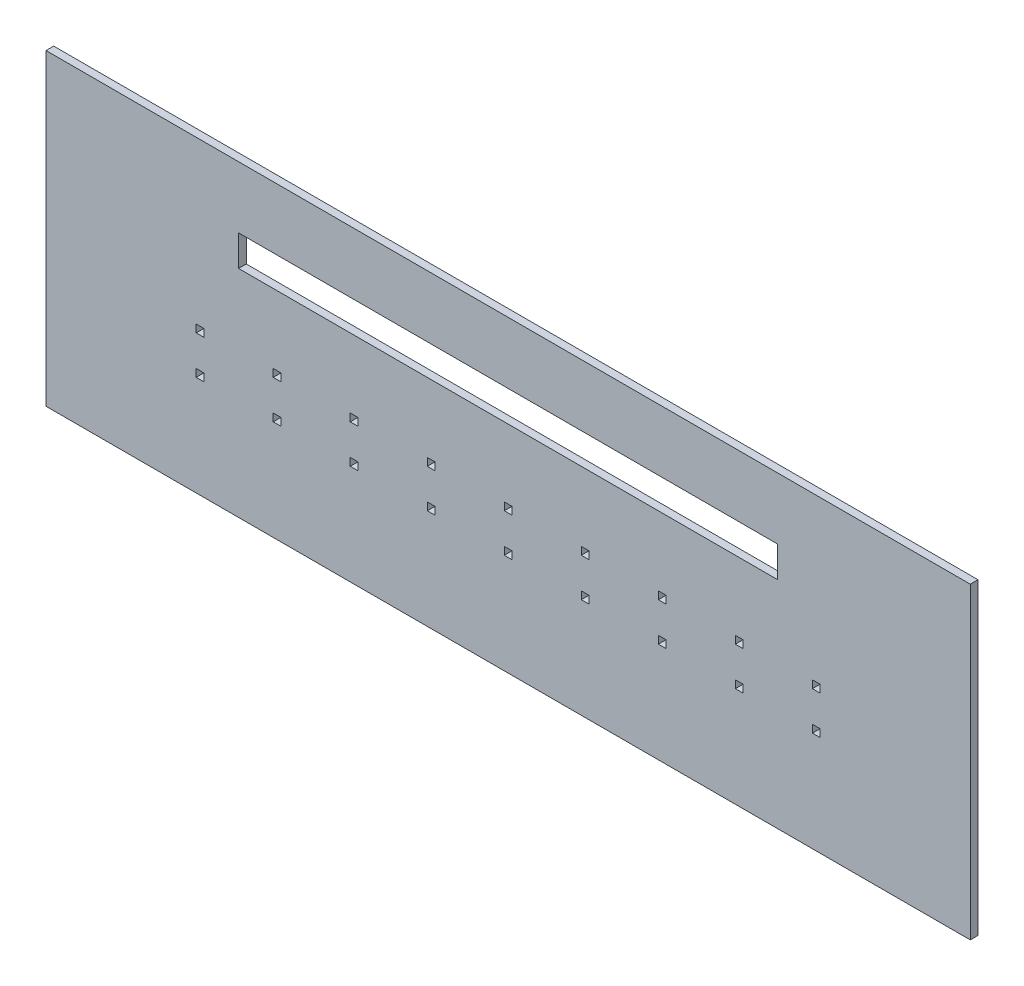
SolidWorks part; units mm, degrees
ref_plane "Front Plane" through (0, 0, 0) normal (0, 0, 1) x (1, 0, 0)
ref_plane "Top Plane" through (0, 0, 0) normal (0, 1, 0) x (1, 0, 0)
ref_plane "Right Plane" through (0, 0, 0) normal (1, 0, 0) x (0, 0, -1)
sketch "Sketch1" plane through (0, 0, 0) normal (0, 0, 1) x (1, 0, 0)
  line L1 (300, 200) -> (-300, 200)
  line L2 (300, 200) -> (300, 0)
  line L3 (300, 0) -> (-300, 0)
  line L4 (-300, 200) -> (-300, 0)
  line L5 (300, 200) -> (-300, 0) construction
  line L6 (300, 0) -> (-300, 200) construction
  point P0 (0, 100)
  dimension "D1" = 600
  dimension "D2" = 200
extrude "Extrude1" add sketch "Sketch1" along normal blind 5
sketch "Sketch2" plane through (0, 0, 5) normal (0, 0, 1) x (1, 0, 0)
  line L0 (0, 0) -> (0, 150) construction
  line L1 (-175, 160) -> (175, 160)
  line L2 (-175, 160) -> (-175, 140)
  line L3 (-175, 140) -> (175, 140)
  line L4 (175, 160) -> (175, 140)
  line L5 (-175, 160) -> (175, 140) construction
  line L6 (-175, 140) -> (175, 160) construction
  point P0 (0, 150)
  dimension "D1" = 20
  dimension "D2" = 350
  dimension "D3" = 150
extrude "Cut-Extrude1" cut sketch "Sketch2" against normal up to next
sketch "Sketch4" plane through (0, 0, 5) normal (0, 0, 1) x (1, 0, 0)
  line L0 (300, 65) -> (-300, 65) construction
  line L1 (300, 0) -> (300, 200) construction
  line L2 (-300, 200) -> (-300, 0) construction
  line L3 (-300, 0) -> (300, 0) construction
  line L4 (-2.5, 70) -> (2.5, 70)
  line L5 (-2.5, 70) -> (-2.5, 65)
  line L6 (-2.5, 65) -> (2.5, 65)
  line L7 (2.5, 70) -> (2.5, 65)
  line L8 (-2.5, 70) -> (2.5, 65) construction
  line L9 (-2.5, 65) -> (2.5, 70) construction
  line L10 (-2.5, 95) -> (2.5, 95)
  line L11 (-2.5, 95) -> (-2.5, 90)
  line L12 (-2.5, 90) -> (2.5, 90)
  line L13 (2.5, 95) -> (2.5, 90)
  line L14 (-2.5, 95) -> (2.5, 90) construction
  line L15 (-2.5, 90) -> (2.5, 95) construction
  line L16 (0, 0) -> (0, 67.5) construction
  line L17 (0, 67.5) -> (0, 92.5) construction
  point P6 (0, 67.5)
  point P11 (0, 92.5)
  dimension "D1" = 5
  dimension "D2" = 5
  dimension "D3" = 20
  dimension "D4" = 65
extrude "Cut-Extrude2" cut sketch "Sketch4" against normal up to next
pattern_linear "LPattern4" count 5 spacing 50 along (-1, 0, 0) count 5 spacing 50 along (1, 0, 0) of "Cut-Extrude2"
